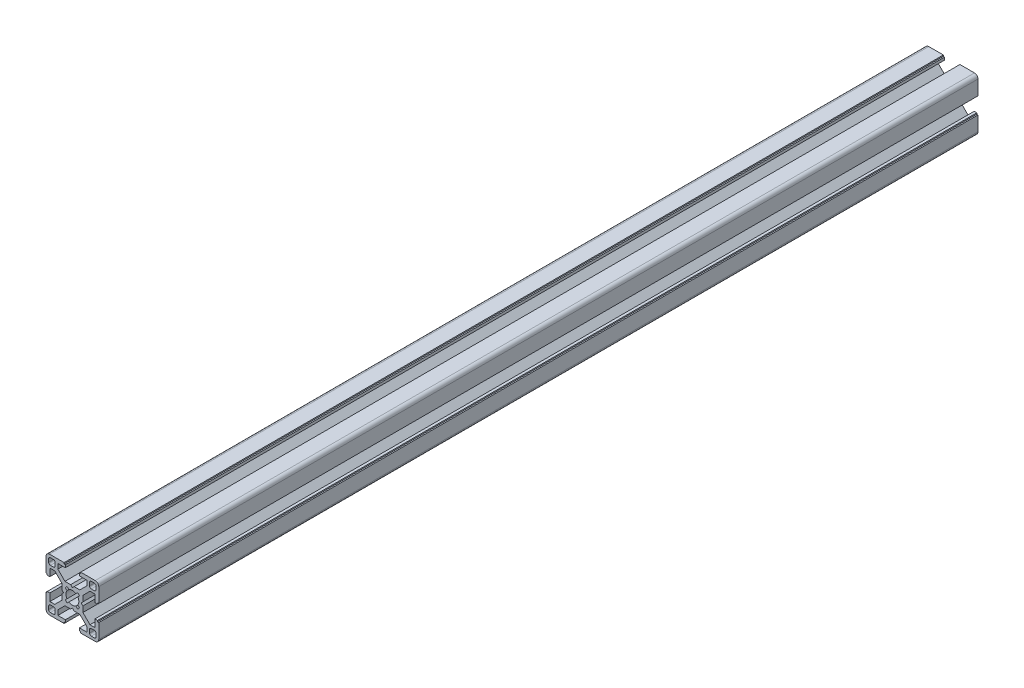
SolidWorks part; units mm, degrees
material "6063-O, Barra estrusa (SS)"
ref_plane "Piano frontale" through (0, 0, 0) normal (0, 0, 1) x (1, 0, 0)
ref_plane "Piano superiore" through (0, 0, 0) normal (0, 1, 0) x (1, 0, 0)
ref_plane "Piano destro" through (0, 0, 0) normal (1, 0, 0) x (0, 0, -1)
sketch "Schizzo1" plane through (0, 0, 0) normal (0, 0, 1) x (1, 0, 0)
  line L0 (-125.0647, 0) -> (53.776, 0) construction
  line L1 (0, -44.8297) -> (0, 95.2781) construction
  line L2 (-15, 13) -> (-15, 4.7)
  line L3 (-15, 4.7) -> (-14.3, 4.7)
  line L4 (-14.3, 4.7) -> (-14.3, 4)
  line L5 (-14.3, 4) -> (-12.8, 4)
  line L6 (-12.8, 4) -> (-12.8, 8.25)
  line L7 (-12.8, 8.25) -> (-10.0178, 8.25)
  line L8 (-10.0178, 8.25) -> (-6, 4.2322)
  line L9 (-6, 4.2322) -> (-6, 1)
  line L10 (-6, 1) -> (-5, 0)
  line L11 (-1, 6) -> (0, 5)
  line L12 (0, 0) -> (-161.3113, 161.3113) construction
  line L13 (-4.2322, 6) -> (-1, 6)
  line L14 (-8.25, 10.0178) -> (-4.2322, 6)
  line L15 (-8.25, 12.8) -> (-8.25, 10.0178)
  line L16 (-4, 12.8) -> (-8.25, 12.8)
  line L17 (-4, 14.3) -> (-4, 12.8)
  line L18 (-4.7, 14.3) -> (-4, 14.3)
  line L19 (-4.7, 15) -> (-4.7, 14.3)
  line L20 (-13, 15) -> (-4.7, 15)
  line L21 (13.5, 10.75) -> (13.5, 12.5)
  line L22 (10.75, 13.5) -> (12.5, 13.5)
  line L23 (9.75, 10.75) -> (9.75, 12.5)
  line L24 (10.75, 9.75) -> (12.5, 9.75)
  line L25 (10.75, -13.5) -> (12.5, -13.5)
  line L26 (13.5, -10.75) -> (13.5, -12.5)
  line L27 (10.75, -9.75) -> (12.5, -9.75)
  line L28 (9.75, -10.75) -> (9.75, -12.5)
  line L29 (-13.5, -10.75) -> (-13.5, -12.5)
  line L30 (-10.75, -13.5) -> (-12.5, -13.5)
  line L31 (-9.75, -10.75) -> (-9.75, -12.5)
  line L32 (-10.75, -9.75) -> (-12.5, -9.75)
  line L33 (1.9955, 3.0562) -> (3.0052, 4.0659)
  line L34 (3.0052, 4.0659) -> (4.0659, 3.0052)
  line L35 (4.0659, 3.0052) -> (3.0562, 1.9955)
  line L36 (3.0562, -1.9955) -> (4.0659, -3.0052)
  line L37 (4.0659, -3.0052) -> (3.0052, -4.0659)
  line L38 (3.0052, -4.0659) -> (1.9955, -3.0562)
  line L39 (-1.9955, -3.0562) -> (-3.0052, -4.0659)
  line L40 (-3.0052, -4.0659) -> (-4.0659, -3.0052)
  line L41 (-4.0659, -3.0052) -> (-3.0562, -1.9955)
  line L42 (1, 6) -> (0, 5)
  line L43 (4.2322, 6) -> (1, 6)
  line L44 (8.25, 10.0178) -> (4.2322, 6)
  line L45 (8.25, 12.8) -> (8.25, 10.0178)
  line L46 (4, 12.8) -> (8.25, 12.8)
  line L47 (12.8, 4) -> (12.8, 8.25)
  line L48 (12.8, 8.25) -> (10.0178, 8.25)
  line L49 (10.0178, 8.25) -> (6, 4.2322)
  line L50 (6, 4.2322) -> (6, 1)
  line L51 (6, 1) -> (5, 0)
  line L52 (6, -1) -> (5, 0)
  line L53 (6, -4.2322) -> (6, -1)
  line L54 (10.0178, -8.25) -> (6, -4.2322)
  line L55 (12.8, -8.25) -> (10.0178, -8.25)
  line L56 (12.8, -4) -> (12.8, -8.25)
  line L57 (4, -12.8) -> (8.25, -12.8)
  line L58 (8.25, -12.8) -> (8.25, -10.0178)
  line L59 (8.25, -10.0178) -> (4.2322, -6)
  line L60 (4.2322, -6) -> (1, -6)
  line L61 (1, -6) -> (0, -5)
  line L62 (-1, -6) -> (0, -5)
  line L63 (-4.2322, -6) -> (-1, -6)
  line L64 (-8.25, -10.0178) -> (-4.2322, -6)
  line L65 (-8.25, -12.8) -> (-8.25, -10.0178)
  line L66 (-4, -12.8) -> (-8.25, -12.8)
  line L67 (-12.8, -4) -> (-12.8, -8.25)
  line L68 (-12.8, -8.25) -> (-10.0178, -8.25)
  line L69 (-10.0178, -8.25) -> (-6, -4.2322)
  line L70 (-6, -4.2322) -> (-6, -1)
  line L71 (-6, -1) -> (-5, 0)
  line L72 (4, 14.3) -> (4, 12.8)
  line L73 (4.7, 14.3) -> (4, 14.3)
  line L74 (4.7, 15) -> (4.7, 14.3)
  line L75 (-3.0562, 1.9955) -> (-4.0659, 3.0052)
  line L76 (-4.0659, 3.0052) -> (-3.0052, 4.0659)
  line L77 (-3.0052, 4.0659) -> (-1.9955, 3.0562)
  line L78 (15, 4.7) -> (14.3, 4.7)
  line L79 (-10.75, 9.75) -> (-12.5, 9.75)
  line L80 (-9.75, 10.75) -> (-9.75, 12.5)
  line L81 (-10.75, 13.5) -> (-12.5, 13.5)
  line L82 (-13.5, 10.75) -> (-13.5, 12.5)
  line L83 (14.3, 4.7) -> (14.3, 4)
  line L84 (14.3, 4) -> (12.8, 4)
  line L85 (14.3, -4) -> (12.8, -4)
  line L86 (14.3, -4.7) -> (14.3, -4)
  line L87 (15, -4.7) -> (14.3, -4.7)
  line L88 (4.7, -15) -> (4.7, -14.3)
  line L89 (4.7, -14.3) -> (4, -14.3)
  line L90 (4, -14.3) -> (4, -12.8)
  line L91 (-4, -14.3) -> (-4, -12.8)
  line L92 (-4.7, -14.3) -> (-4, -14.3)
  line L93 (-4.7, -15) -> (-4.7, -14.3)
  line L94 (-15, -4.7) -> (-14.3, -4.7)
  line L95 (-14.3, -4.7) -> (-14.3, -4)
  line L96 (-14.3, -4) -> (-12.8, -4)
  line L97 (4, 14.3) -> (4, 12.8)
  line L98 (4.7, 14.3) -> (4, 14.3)
  line L99 (4.7, 15) -> (4.7, 14.3)
  line L100 (15, 4.7) -> (14.3, 4.7)
  line L101 (14.3, 4.7) -> (14.3, 4)
  line L102 (14.3, 4) -> (12.8, 4)
  line L103 (13, 15) -> (4.7, 15)
  line L104 (15, 13) -> (15, 4.7)
  line L105 (14.3, -4) -> (12.8, -4)
  line L106 (14.3, -4.7) -> (14.3, -4)
  line L107 (15, -4.7) -> (14.3, -4.7)
  line L108 (4.7, -15) -> (4.7, -14.3)
  line L109 (4.7, -14.3) -> (4, -14.3)
  line L110 (4, -14.3) -> (4, -12.8)
  line L111 (15, -13) -> (15, -4.7)
  line L112 (13, -15) -> (4.7, -15)
  line L113 (-4, -14.3) -> (-4, -12.8)
  line L114 (-4.7, -14.3) -> (-4, -14.3)
  line L115 (-4.7, -15) -> (-4.7, -14.3)
  line L116 (-15, -4.7) -> (-14.3, -4.7)
  line L117 (-14.3, -4.7) -> (-14.3, -4)
  line L118 (-14.3, -4) -> (-12.8, -4)
  line L119 (-13, -15) -> (-4.7, -15)
  line L120 (-15, -13) -> (-15, -4.7)
  arc A0 (-3.65, 0) -> (-3.0562, 1.9955) centre (0, 0) cw
  arc A1 (-1.9955, 3.0562) -> (0, 3.65) centre (0, 0) cw
  arc A2 (-13, 15) -> (-15, 13) centre (-13, 13) ccw
  arc A3 (-13.5, 10.75) -> (-12.5, 9.75) centre (-12.5, 10.75) ccw
  arc A4 (-9.75, 10.75) -> (-10.75, 9.75) centre (-10.75, 10.75) cw
  arc A5 (-10.75, 13.5) -> (-9.75, 12.5) centre (-10.75, 12.5) cw
  arc A6 (-12.5, 13.5) -> (-13.5, 12.5) centre (-12.5, 12.5) ccw
  arc A7 (13.5, 12.5) -> (12.5, 13.5) centre (12.5, 12.5) ccw
  arc A8 (13.5, 10.75) -> (12.5, 9.75) centre (12.5, 10.75) cw
  arc A9 (10.75, 9.75) -> (9.75, 10.75) centre (10.75, 10.75) cw
  arc A10 (10.75, 13.5) -> (9.75, 12.5) centre (10.75, 12.5) ccw
  arc A11 (12.5, -13.5) -> (13.5, -12.5) centre (12.5, -12.5) ccw
  arc A12 (10.75, -13.5) -> (9.75, -12.5) centre (10.75, -12.5) cw
  arc A13 (9.75, -10.75) -> (10.75, -9.75) centre (10.75, -10.75) cw
  arc A14 (13.5, -10.75) -> (12.5, -9.75) centre (12.5, -10.75) ccw
  arc A15 (-13.5, -12.5) -> (-12.5, -13.5) centre (-12.5, -12.5) ccw
  arc A16 (-13.5, -10.75) -> (-12.5, -9.75) centre (-12.5, -10.75) cw
  arc A17 (-10.75, -9.75) -> (-9.75, -10.75) centre (-10.75, -10.75) cw
  arc A18 (-10.75, -13.5) -> (-9.75, -12.5) centre (-10.75, -12.5) ccw
  arc A19 (0, 3.65) -> (1.9955, 3.0562) centre (0, 0) cw
  arc A20 (3.0562, 1.9955) -> (3.65, 0) centre (0, 0) cw
  arc A21 (3.65, 0) -> (3.0562, -1.9955) centre (0, 0) cw
  arc A22 (1.9955, -3.0562) -> (0, -3.65) centre (0, 0) cw
  arc A23 (0, -3.65) -> (-1.9955, -3.0562) centre (0, 0) cw
  arc A24 (-3.0562, -1.9955) -> (-3.65, 0) centre (0, 0) cw
  arc A25 (15, 13) -> (13, 15) centre (13, 13) ccw
  arc A26 (13, -15) -> (15, -13) centre (13, -13) ccw
  arc A27 (-15, -13) -> (-13, -15) centre (-13, -13) ccw
  point P70 (0, 0)
  point P86 (0, 0)
  point P88 (-15, 15)
  point P100 (-9.75, 9.75)
  point P107 (0, 0)
  point P144 (0, 0)
  point P169 (0, 0)
  point P197 (0, 0)
  dimension "D11" = 7.3
  dimension "D14" = 2
  dimension "D17" = 1
  dimension "D1" = 45
  dimension "D2" = 8
  dimension "D3" = 16.5
  dimension "D4" = 9
  dimension "D5" = 2.2
  dimension "D6" = 15
  dimension "D7" = 2.5
  dimension "D8" = 8.3
  dimension "D9" = 2
  dimension "D12" = 5
  dimension "D13" = 1.5
  dimension "D15" = 1.5
  dimension "D16" = 1.5
  dimension "D10" = 4
  dimension "D18" = 4
  dimension "D19" = 4
  dimension "D20" = 4
  dimension "D21" = 4
extrude "Estrusione-Estrusione2" add sketch "Schizzo1" along normal blind 500 contours L120 A27 L119 L93 L92 L91 L66 L65 L64 L63 L62 L61 L60 L59 L58 L57 L90 L89 L88 L112 A26 L111 L87 L86 L85 L56 L55 L54 L53 L52 L51 L50 L49 L48 L47 L84 L83 L78 L104 A25 L103 L74 L73 L72 L46 L45 L44 L43 L42 L11 L13
